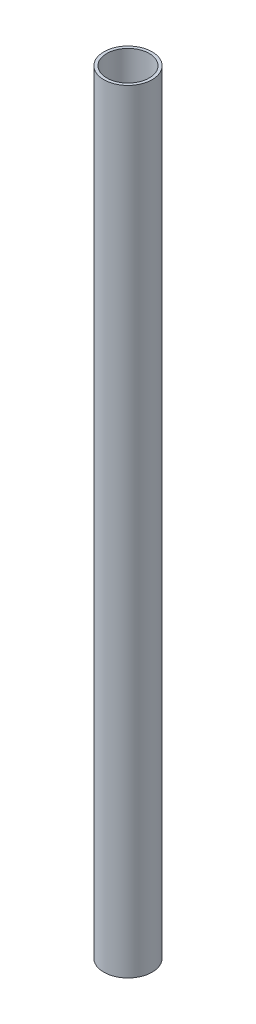
SolidWorks part; units mm, degrees
ref_plane "Front Plane" through (0, 0, 0) normal (0, 0, 1) x (1, 0, 0)
ref_plane "Top Plane" through (0, 0, 0) normal (0, 1, 0) x (1, 0, 0)
ref_plane "Right Plane" through (0, 0, 0) normal (1, 0, 0) x (0, 0, -1)
sketch "Sketch3" plane through (0, 0, 0) normal (0, 1, 0) x (1, 0, 0)
  circle A0 centre (0, 0) radius 12.5
  dimension "D1" = 25
extrude "Extrude-Thin1" add sketch "Sketch3" along normal blind 400 thin thin type one direction reverse wall 1.5
